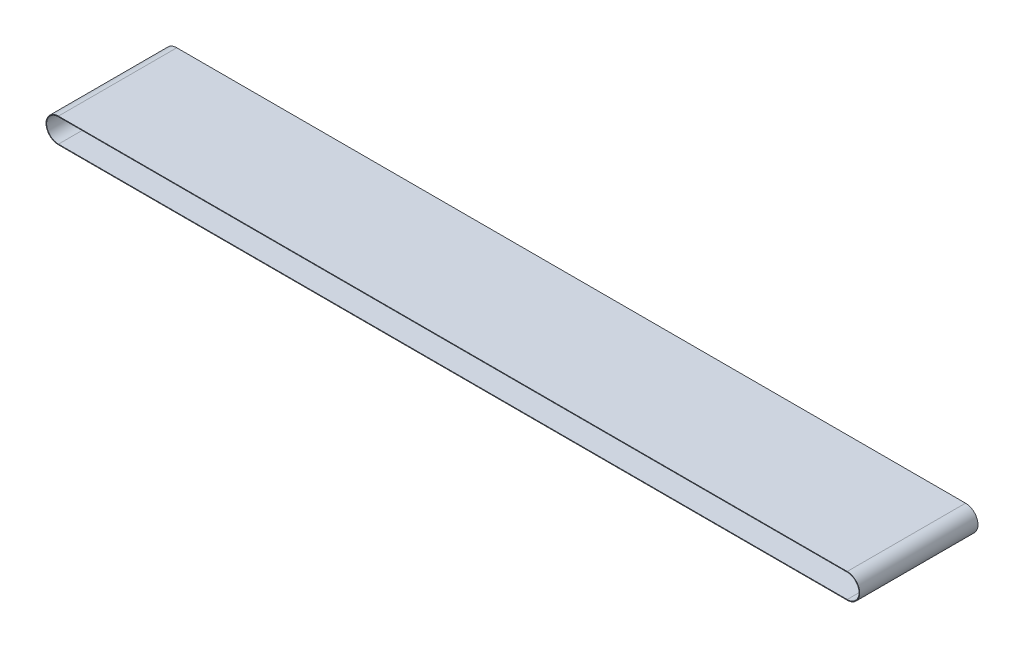
SolidWorks part; units mm, degrees
ref_plane "Front Plane" through (0, 0, 0) normal (0, 0, 1) x (1, 0, 0)
ref_plane "Top Plane" through (0, 0, 0) normal (0, 1, 0) x (1, 0, 0)
ref_plane "Right Plane" through (0, 0, 0) normal (1, 0, 0) x (0, 0, -1)
sketch "Sketch1" plane through (0, 0, 0) normal (0, 0, 1) x (1, 0, 0)
  line L0 (0, 0) -> (1000, 0) construction
  line L1 (0, 15) -> (1000, 15)
  line L2 (0, -15) -> (1000, -15)
  line L3 (0, 15.8) -> (1000, 15.8)
  line L4 (0, -15.8) -> (1000, -15.8)
  arc A0 (0, 15) -> (0, -15) centre (0, 0) ccw
  arc A1 (1000, -15) -> (1000, 15) centre (1000, 0) ccw
  arc A2 (1000, -15.8) -> (1000, 15.8) centre (1000, 0) ccw
  arc A3 (0, 15.8) -> (0, -15.8) centre (0, 0) ccw
  point P3 (500, 0)
  dimension "L" = 1000
  dimension "FIX_1" = 30
  dimension "MSM_11" = 0.8
extrude "Boss-Extrude1" add sketch "Sketch1" along normal mid plane 150
